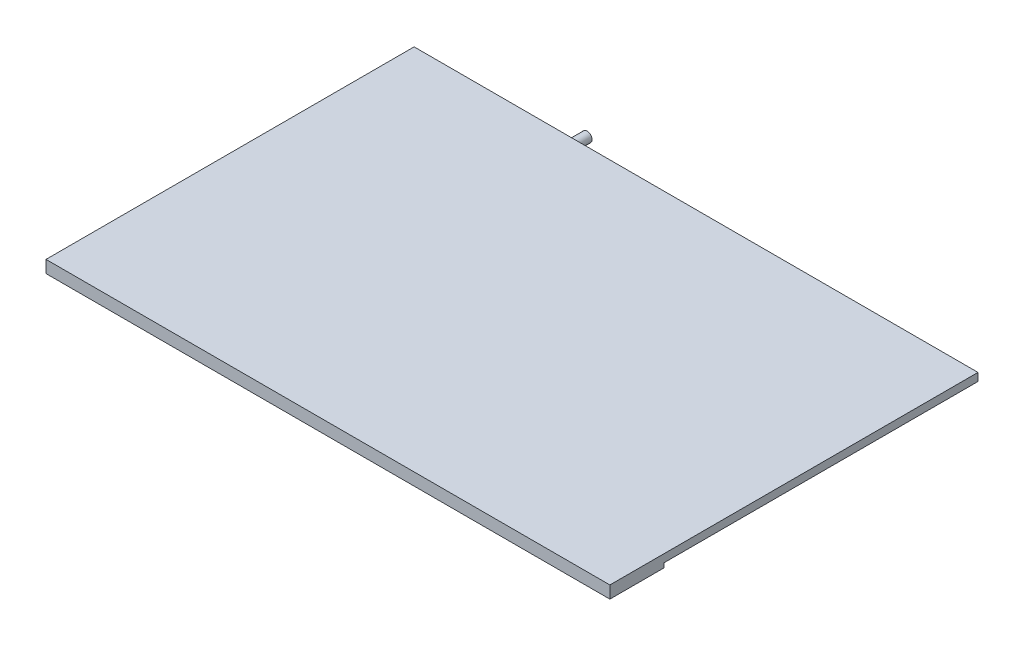
SolidWorks part; units mm, degrees
ref_plane "Front Plane" through (0, 0, 0) normal (0, 0, 1) x (1, 0, 0)
ref_plane "Top Plane" through (0, 0, 0) normal (0, 1, 0) x (1, 0, 0)
ref_plane "Right Plane" through (0, 0, 0) normal (1, 0, 0) x (0, 0, -1)
sketch "Sketch1" plane through (0, 0, 0) normal (0, 1, 0) x (1, 0, 0)
  line L1 (-114.5, 74.75) -> (114.5, 74.75)
  line L2 (-114.5, 74.75) -> (-114.5, -74.75)
  line L3 (-114.5, -74.75) -> (114.5, -74.75)
  line L4 (114.5, 74.75) -> (114.5, -74.75)
  point P4 (0, 74.75)
  point P5 (114.5, 0)
  dimension "D1" = 149.5
  dimension "D2" = 229
extrude "Boss-Extrude1" add sketch "Sketch1" along normal blind 3.2
sketch "Sketch2" plane through (0, 3.2, 0) normal (0, 1, 0) x (1, 0, 0)
  line L0 (-114.5, -52.75) -> (114.5, -52.75)
  line L4 (-114.5, 74.75) -> (-114.5, -74.75)
  line L5 (-114.5, -74.75) -> (114.5, -74.75)
  line L6 (114.5, -74.75) -> (114.5, 74.75)
  line L7 (114.5, 74.75) -> (-114.5, 74.75)
  line L8 (-114.5, 74.75) -> (-114.5, -74.75)
  line L9 (-114.5, -74.75) -> (114.5, -74.75)
  line L10 (114.5, -74.75) -> (114.5, 74.75)
  line L11 (114.5, 74.75) -> (-114.5, 74.75)
  line M6 (-114.5, 74.75) -> (-114.5, -74.75)
  line M7 (-114.5, -74.75) -> (114.5, -74.75)
  line M8 (114.5, -74.75) -> (114.5, 74.75)
  dimension "D2" = 22
  dimension "D1" = 0
extrude "Boss-Extrude2" add sketch "Sketch2" against normal blind 5 contours L0 M6 M7 M8
sketch "Sketch3" plane through (0, -1.8, 0) normal (0, -1, 0) x (1, 0, 0)
  line L0 (-114.5, -74.75) -> (-114.5, 52.75) construction
  line L1 (-67.5, 61.55) -> (-41, 61.55)
  line L2 (-67.5, 61.55) -> (-67.5, 39.55)
  line L3 (-67.5, 39.55) -> (-41, 39.55)
  line L4 (-41, 61.55) -> (-41, 39.55)
  line L5 (-114.5, 74.75) -> (114.5, 74.75) construction
  line L6 (114.5, -74.75) -> (-114.5, -74.75) construction
  line L7 (-48.75, 39.55) -> (-59.75, 39.55)
  line L8 (-48.75, 39.55) -> (-48.75, -74.75)
  line L9 (-48.75, -74.75) -> (-59.75, -74.75)
  line L10 (-59.75, 39.55) -> (-59.75, -74.75)
  point P15 (-54.25, 61.55)
  point P16 (-54.25, -74.75)
  line M9 (-114.5, 52.75) -> (114.5, 52.75)
  dimension "D1" = 47
  dimension "D2" = 26.5
  dimension "D3" = 22
  dimension "D4" = 13.2
  dimension "D5" = 11
extrude "Boss-Extrude3" add sketch "Sketch3" along normal blind 3 contours L4 L2 L3 M9 | L4 L1 L2 M9 | L3 L10 L9 L8
sketch "Sketch4" plane through (0, 0, -74.75) normal (0, 0, -1) x (-1, 0, 0)
  circle A0 centre (54.25, -3.3) radius 2
  dimension "D1" = 4
extrude "Boss-Extrude4" add sketch "Sketch4" along normal blind 10
